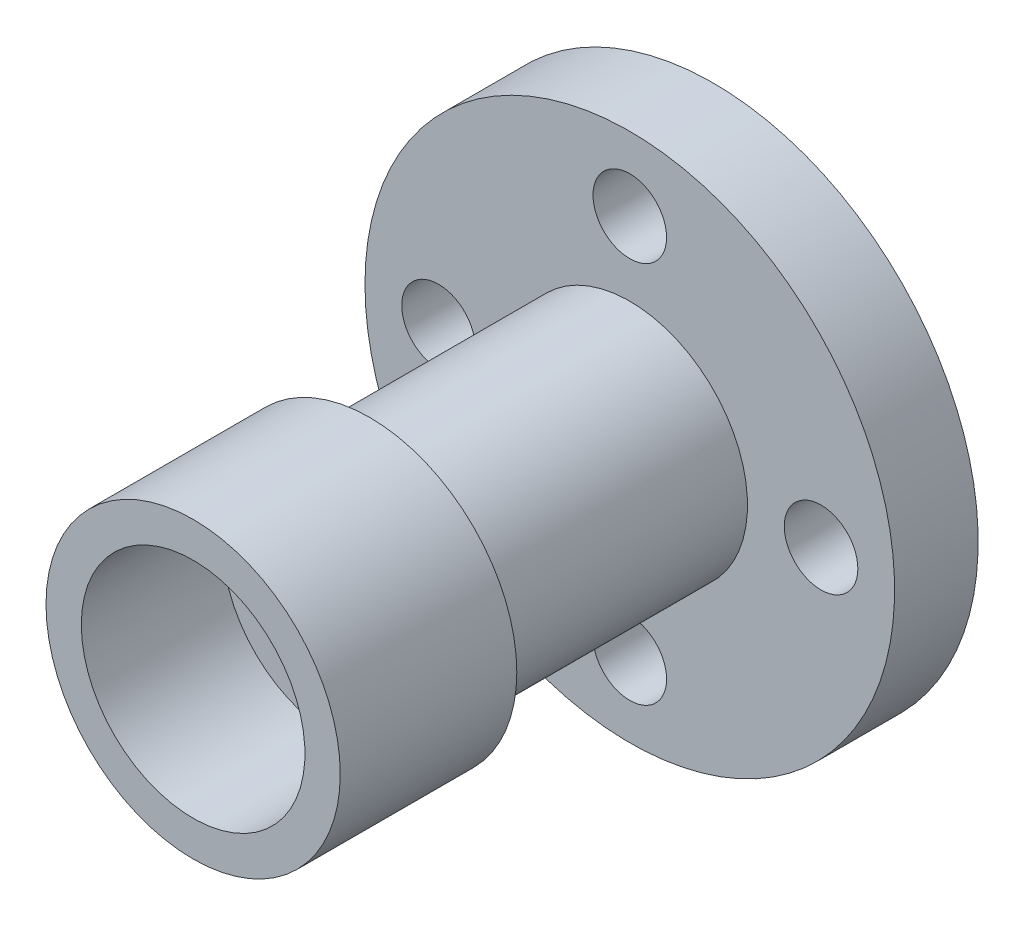
SolidWorks part; units mm, degrees
ref_plane "Alzado" through (0, 0, 0) normal (0, 0, 1) x (1, 0, 0)
ref_plane "Planta" through (0, 0, 0) normal (0, 1, 0) x (1, 0, 0)
ref_plane "Vista lateral" through (0, 0, 0) normal (1, 0, 0) x (0, 0, -1)
sketch "Croquis2" plane through (0, 0, 0) normal (1, 0, 0) x (0, 0, -1)
  line L0 (0, 18.5) -> (0, 45)
  line L1 (0, 45) -> (-14.2, 45)
  line L5 (-14.2, 45) -> (-14.2, 20)
  line L6 (-14.2, 20) -> (-58.4, 20)
  line L8 (-58.4, 25) -> (-58.4, 20)
  line L9 (-58.4, 25) -> (-88.4, 25)
  line L11 (-88.4, 25) -> (-88.4, 19)
  line L12 (-88.4, 19) -> (-64.4, 19)
  line L13 (-64.4, 19) -> (-64.4, 15)
  line L14 (0, 0) -> (-88.4, 0) construction
  line L15 (-64.4, 15) -> (-3, 15)
  line L18 (0, 18.5) -> (-3, 15)
  dimension "D1" = 14.2
  dimension "D2" = 44.2
  dimension "D3" = 20
  dimension "D4" = 15
  dimension "D5" = 25
  dimension "D6" = 45
  dimension "D7" = 30
revolve "Revolución2" add sketch "Croquis2" angle 360 about L14
sketch "Croquis4" plane through (0, 0, 0) normal (0, 0, -1) x (-1, 0, 0)
  line L0 (0, 0) -> (0, 32.5)
  circle A0 centre (0, 32.5) radius 6.25
  circle A1 centre (32.5, 0) radius 6.25
  circle A2 centre (0, -32.5) radius 6.25
  circle A3 centre (-32.5, 0) radius 6.25
  point P13 (0, 0)
  dimension "D1" = 12.5
  dimension "D2" = 32.5
  dimension "D3" = 4
extrude "Cortar-Extruir2" cut sketch "Croquis4" along direction (0, 0, 1) on the side against the normal through all contours A0 | A3 | A1 | A2
